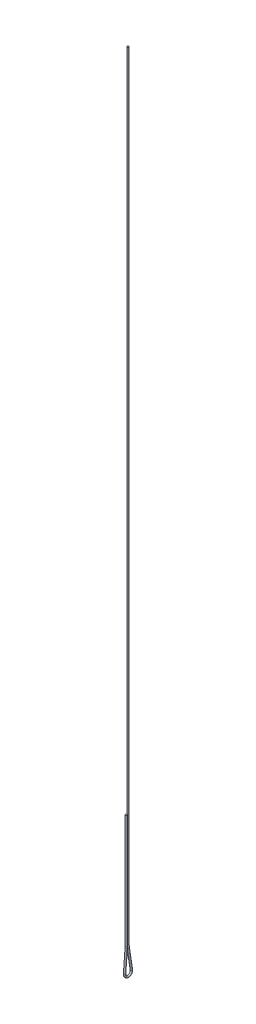
SolidWorks part; units mm, degrees
ref_plane "Front Plane" through (0, 0, 0) normal (0, 0, 1) x (1, 0, 0)
ref_plane "Top Plane" through (0, 0, 0) normal (0, 1, 0) x (1, 0, 0)
ref_plane "Right Plane" through (0, 0, 0) normal (1, 0, 0) x (0, 0, -1)
sketch "Sketch1" plane through (0, 0, 0) normal (1, 0, 0) x (0, 0, -1)
  line L1 (0, 21.5085) -> (0, 700)
  line L2 (0, 55) -> (0, -55) construction
  line L3 (55, 0) -> (-55, 0) construction
  line L4 (0.2263, 18.5085) -> (2.9661, 0.45)
  line L5 (-1.5, 20.7532) -> (-1.5, 120)
  line L6 (-1.5566, 19.2489) -> (-2.9915, 0.2256)
  circle A0 centre (0, 0) radius 2 construction
  arc A1 (-2.9915, 0.2256) -> (2.9661, 0.45) centre (0, 0) ccw
  arc A2 (0, 21.5085) -> (0.2263, 18.5085) centre (20, 21.5085) ccw
  arc A3 (-1.5, 20.7532) -> (-1.5566, 19.2489) centre (-21.5, 20.7532) cw
  point P15 (0, 20)
  point P18 (-1.5, 20)
  dimension "D1" = 4
  dimension "D2" = 6
  dimension "D8" = 20
  dimension "D3" = 20
  dimension "D4" = 680
  dimension "D5" = 1.5
  dimension "D6" = 100
  dimension "D7" = 20
ref_plane "Plane1" through (0, 120, 1.5) normal (0, 1, 0) x (-1, 0, 0)
sketch "Sketch2" plane through (0, 120, 1.5) normal (0, 1, 0) x (-1, 0, 0)
  circle A0 centre (0, 0) radius 0.75
  dimension "D1" = 1.5
sweep "Sweep1" add profiles "Sketch2" path "Sketch1"
